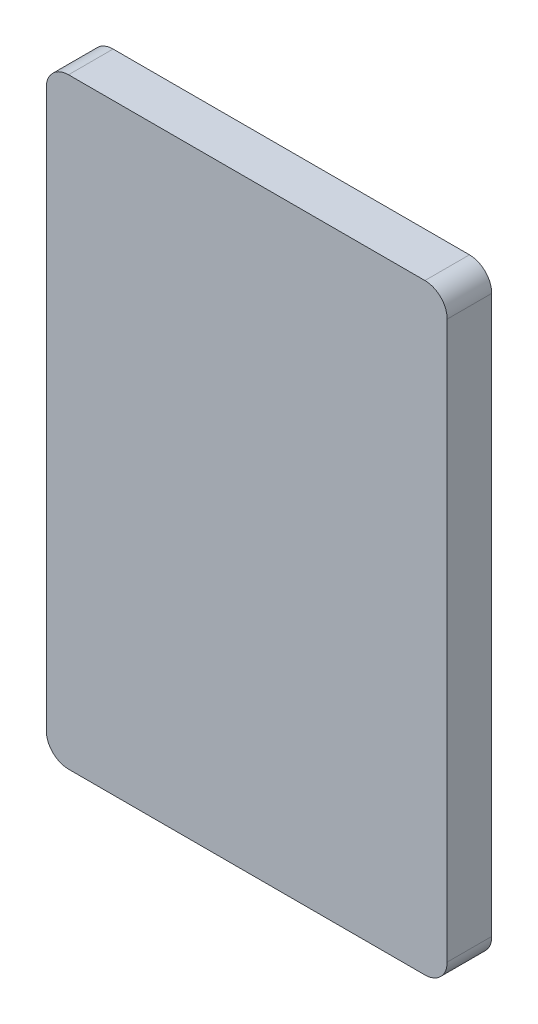
SolidWorks part; units mm, degrees
material "Polycarbonate (PC)"
ref_plane "Front Plane" through (0, 0, 0) normal (0, 0, 1) x (1, 0, 0)
ref_plane "Top Plane" through (0, 0, 0) normal (0, 1, 0) x (1, 0, 0)
ref_plane "Right Plane" through (0, 0, 0) normal (1, 0, 0) x (0, 0, -1)
sketch "Sketch1" plane through (0, 0, 0) normal (0, 0, 1) x (1, 0, 0)
  line L1 (9, -13.5) -> (-9, -13.5)
  line L2 (9, -13.5) -> (9, 13.5)
  line L3 (9, 13.5) -> (-9, 13.5)
  line L4 (-9, -13.5) -> (-9, 13.5)
  line L5 (9, -13.5) -> (-9, 13.5) construction
  line L6 (9, 13.5) -> (-9, -13.5) construction
  point P0 (0, 0)
  dimension "D1" = 18
  dimension "D2" = 27
extrude "Base" add sketch "Sketch1" along normal blind 2
fillet "Fillet" radius 1 4 edges at (9, 13.5, 1) (9, -13.5, 1) (-9, -13.5, 1) (-9, 13.5, 1)
